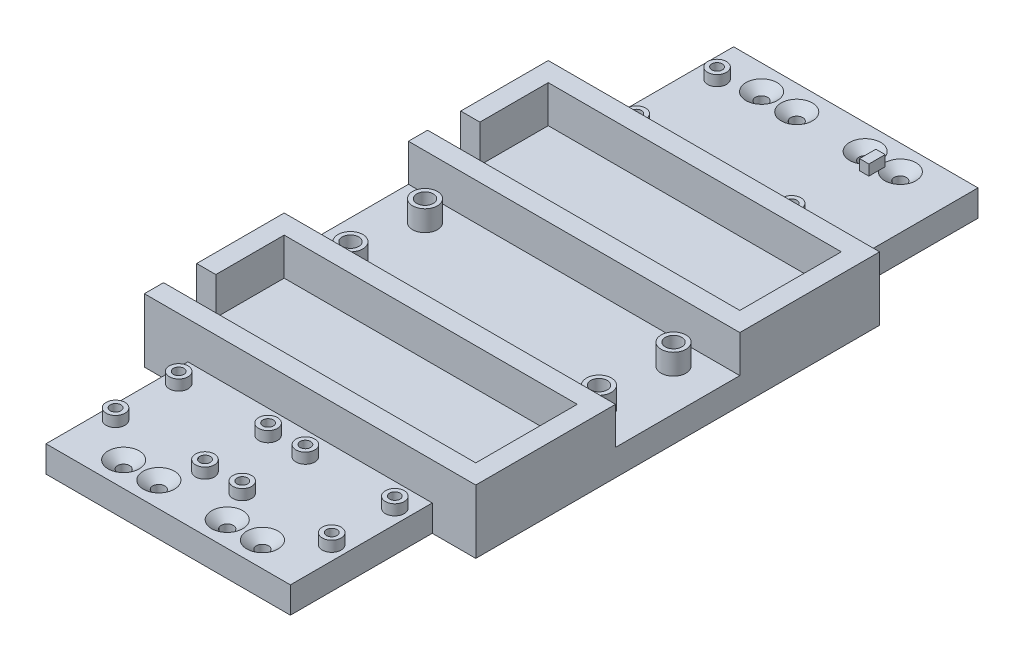
SolidWorks part; units mm, degrees
ref_plane "Front Plane" through (0, 0, 0) normal (0, 0, 1) x (1, 0, 0)
ref_plane "Top Plane" through (0, 0, 0) normal (0, 1, 0) x (1, 0, 0)
ref_plane "Right Plane" through (0, 0, 0) normal (1, 0, 0) x (0, 0, -1)
sketch "Sketch2" plane through (0, 0, 0) normal (0, 1, 0) x (1, 0, 0)
  line L1 (40, -83) -> (-40, -83)
  line L2 (40, -83) -> (40, 83)
  line L3 (40, 83) -> (-40, 83)
  line L4 (-40, -83) -> (-40, 83)
  line L5 (40, -83) -> (-40, 83) construction
  line L6 (40, 83) -> (-40, -83) construction
  point P0 (0, 0)
  dimension "D1" = 80
  dimension "D2" = 166
extrude "Boss-Extrude1" add sketch "Sketch2" along normal blind 6.35
sketch "Sketch3" plane through (0, 6.35, 0) normal (0, 1, 0) x (1, 0, 0)
  line L3 (16.755, 77) -> (8.255, 77)
  line L4 (0, 0) -> (0, 77)
  line L6 (0, 77) -> (8.255, 77)
  dimension "D1" = 8.255
  dimension "D2" = 8.5
  dimension "D3" = 77
hole_wizard "CSK for #4 Flat Head Machine Screw (100)1" positions "Sketch4" profile "Sketch5" countersink size "#4" standard "ANSI Inch" end condition through all
sketch "Sketch4" plane through (0, 6.35, 0) normal (0, 1, 0) x (1, 0, 0)
  point P0 (16.755, 77)
  point P3 (8.255, 77)
sketch "Sketch5" plane through (16.755, 6.35, -77) normal (1, 0, 0) x (0, 0, 1)
  line L0 (0, 0) -> (0, 6.35)
  line L1 (0, 6.35) -> (1.4732, 6.35)
  line L2 (1.4732, 6.35) -> (1.4732, 1.9236)
  line L3 (1.4732, 1.9236) -> (3.7657, 0)
  line L5 (3.7657, 0) -> (0, 0)
  line L6 (-1.4732, 1.9236) -> (-3.7657, 0) construction
  line L11 (0, -6.35) -> (0, 107.95) construction
  dimension "Thru Hole Dia." = 2.9464
  dimension "Thru Hole Depth" = 6.35
  dimension "Near C'Sink Dia." = 7.5313
  dimension "Near C'Sink Angle" = 100
mirror "Mirror1" about plane through (0, 0, 0) normal (0, 0, 1) of "CSK for #4 Flat Head Machine Screw (100)1"
mirror "Mirror2" about plane through (0, 0, 0) normal (1, 0, 0) of "Mirror1", "CSK for #4 Flat Head Machine Screw (100)1"
sketch "Sketch7" plane through (0, 6.35, 0) normal (0, 1, 0) x (1, 0, 0)
  line L0 (-30, 9) -> (30, 9)
  line L1 (30, 9) -> (30, -9)
  line L2 (30, -9) -> (-30, -9)
  line L3 (-30, -9) -> (-30, 9)
  line L4 (-4.5, -69.62) -> (-26.09, -69.62)
  line L5 (-26.09, -69.62) -> (-26.09, -54.38)
  line L6 (-26.09, -54.38) -> (-4.5, -54.38)
  line L7 (-4.5, -54.38) -> (-4.5, -69.62)
  line L8 (4.5, -69.62) -> (4.5, -54.38)
  line L9 (4.5, -54.38) -> (26.09, -54.38)
  line L10 (26.09, -54.38) -> (26.09, -69.62)
  line L11 (26.09, -69.62) -> (4.5, -69.62)
  line L13 (0, -9) -> (0, 0) construction
  line L14 (-24.75, 54.75) -> (12.75, 54.75)
  line L15 (12.75, 54.75) -> (12.75, 74.25)
  line L16 (12.75, 74.25) -> (-24.75, 74.25)
  line L17 (-24.75, 74.25) -> (-24.75, 54.75)
  line L18 (12.75, 64.5) -> (0, 64.5)
  line L19 (0, 0) -> (-30, 0) construction
  line L20 (-4.5, -62) -> (4.5, -62) construction
  line L21 (0, -62) -> (0, -9) construction
  line L22 (0, 64.5) -> (0, 0) construction
  point P14 (4.5, -62)
  dimension "D2" = 64.5
  dimension "D3" = 21.59
  dimension "D4" = 15.24
  dimension "D5" = 18
  dimension "D6" = 19.5
  dimension "D7" = 15.24
  dimension "D8" = 37.5
  dimension "D9" = 9
  dimension "D10" = 60
  dimension "D11" = 53
  dimension "D12" = 12.75
sketch "Sketch9" plane through (0, 6.35, 0) normal (0, 1, 0) x (1, 0, 0)
  circle A0 centre (-30, 9) radius 2
  circle A1 centre (-30, -9) radius 2
  circle A2 centre (30, -9) radius 2
  circle A3 centre (30, 9) radius 2
  circle A4 centre (-30, -9) radius 3
  circle A5 centre (-30, 9) radius 3
  circle A6 centre (30, 9) radius 3
  circle A7 centre (30, -9) radius 3
  dimension "D1" = 4
  dimension "D2" = 1
extrude "Boss-Extrude3" add sketch "Sketch9" along normal blind 5
sketch "Sketch15" plane through (0, 6.35, 0) normal (0, 1, 0) x (1, 0, 0)
  line L0 (-35.375, 44.125) -> (35.375, 44.125)
  line L1 (35.375, 44.125) -> (35.375, 19.625)
  line L2 (35.375, 19.625) -> (-40, 19.625)
  line L3 (-35.375, 27.625) -> (-35.375, 44.125)
  line L4 (35.375, 31.875) -> (40, 31.875) construction
  line L5 (40, 15) -> (-40, 15)
  line L6 (-40, 83) -> (-40, -83) construction
  line L7 (40, -83) -> (40, 83) construction
  line L8 (-40, 15) -> (-40, 19.625)
  line L9 (-40, 48.75) -> (40, 48.75)
  line L10 (40, 48.75) -> (40, 15)
  line L11 (-35.375, 27.625) -> (-40, 27.625)
  line L13 (-40, 27.625) -> (-40, 48.75)
  line L14 (0, 48.75) -> (0, 44.125) construction
  line L15 (0, 15) -> (0, 19.625) construction
  line L16 (0, 15) -> (0, 0) construction
  line L17 (0, 0) -> (0, -15) construction
  line L18 (-40, -15) -> (40, -15)
  line L19 (40, -15) -> (40, -48.75)
  line L20 (40, -48.75) -> (-40, -48.75)
  line L21 (-40, -48.75) -> (-40, -44.125)
  line L22 (-40, -44.125) -> (35.375, -44.125)
  line L23 (35.375, -44.125) -> (35.375, -19.625)
  line L24 (35.375, -19.625) -> (-35.375, -19.625)
  line L25 (-35.375, -19.625) -> (-35.375, -36.125)
  line L26 (-35.375, -36.125) -> (-40, -36.125)
  line L27 (-40, -36.125) -> (-40, -15)
  line L28 (0, -15) -> (0, -19.625) construction
  point P35 (0, -15)
  dimension "D1" = 70.75
  dimension "D2" = 24.5
  dimension "D3" = 15
  dimension "D4" = 8
extrude "Boss-Extrude5" add sketch "Sketch15" along normal blind 9
sketch "Sketch10" plane through (0, 6.35, 0) normal (0, 1, 0) x (1, 0, 0)
  line L1 (11.625, 72.2784) -> (13.875, 72.2784)
  line L2 (11.625, 72.2784) -> (11.625, 76.2216)
  line L3 (11.625, 76.2216) -> (13.875, 76.2216)
  line L4 (13.875, 72.2784) -> (13.875, 76.2216)
  line L5 (11.625, 72.2784) -> (13.875, 76.2216) construction
  line L6 (11.625, 76.2216) -> (13.875, 72.2784) construction
  circle A0 centre (-4.5, -54.38) radius 1.27
  circle A1 centre (-4.5, -69.62) radius 1.27
  circle A2 centre (-26.09, -69.62) radius 1.27
  circle A3 centre (-26.09, -54.38) radius 1.27
  circle A4 centre (4.5, -54.38) radius 1.27
  circle A5 centre (4.5, -69.62) radius 1.27
  circle A6 centre (26.09, -69.62) radius 1.27
  circle A7 centre (26.09, -54.38) radius 1.27
  circle A8 centre (-4.5, -54.38) radius 2.27
  circle A9 centre (-4.5, -69.62) radius 2.27
  circle A10 centre (-26.09, -54.38) radius 2.27
  circle A11 centre (-26.09, -69.62) radius 2.27
  circle A12 centre (4.5, -54.38) radius 2.27
  circle A13 centre (4.5, -69.62) radius 2.27
  circle A14 centre (26.09, -69.62) radius 2.27
  circle A15 centre (26.09, -54.38) radius 2.27
  circle A16 centre (12.75, 54.75) radius 1.27
  circle A17 centre (12.75, 54.75) radius 2.27
  circle A18 centre (12.75, 74.25) radius 1.27 construction
  circle A19 centre (12.75, 74.25) radius 2.27 construction
  circle A20 centre (-24.75, 74.25) radius 1.27
  circle A21 centre (-24.75, 54.75) radius 1.27
  circle A22 centre (-24.75, 54.75) radius 2.27
  circle A23 centre (-24.75, 74.25) radius 2.27
  dimension "D1" = 2.54
  dimension "D2" = 1
  dimension "D3" = 2.25
extrude "Boss-Extrude4" add sketch "Sketch10" along normal blind 2.54
sketch "Sketch11" plane through (0, 6.35, 0) normal (0, 1, 0) x (1, 0, 0)
  circle A0 centre (-30, -9) radius 2
  circle A1 centre (-30, 9) radius 2
  circle A2 centre (26.09, -54.38) radius 1.27
  circle A3 centre (26.09, -69.62) radius 1.27
  circle A4 centre (4.5, -54.38) radius 1.27
  circle A5 centre (4.5, -69.62) radius 1.27
  circle A6 centre (30, 9) radius 2
  circle A7 centre (30, -9) radius 2
  circle A8 centre (-26.09, -69.62) radius 1.27
  circle A9 centre (-26.09, -54.38) radius 1.27
  circle A10 centre (-4.5, -69.62) radius 1.27
  circle A11 centre (-4.5, -54.38) radius 1.27
  circle A12 centre (-30, -9) radius 2 construction
  circle A13 centre (-4.5, -54.38) radius 1.27 construction
  circle A14 centre (12.75, 74.25) radius 1.27 construction
  circle A15 centre (12.75, 54.75) radius 1.27
  circle A16 centre (-24.75, 54.75) radius 1.27
  circle A17 centre (-24.75, 74.25) radius 1.27
extrude "Cut-Extrude1" cut sketch "Sketch11" against normal through all
sketch "Sketch12" plane through (0, 0, 0) normal (0, -1, 0) x (1, 0, 0)
  line L1 (-23.59, 52.9366) -> (-23.59, 55.8234)
  line L2 (-23.59, 55.8234) -> (-26.09, 57.2668)
  line L3 (-26.09, 57.2668) -> (-28.59, 55.8234)
  line L4 (-28.59, 55.8234) -> (-28.59, 52.9366)
  line L5 (-28.59, 52.9366) -> (-26.09, 51.4932)
  line L6 (-26.09, 51.4932) -> (-23.59, 52.9366)
  line L7 (-2, 52.9366) -> (-2, 55.8234)
  line L8 (-2, 55.8234) -> (-4.5, 57.2668)
  line L9 (-4.5, 57.2668) -> (-7, 55.8234)
  line L10 (-7, 55.8234) -> (-7, 52.9366)
  line L11 (-7, 52.9366) -> (-4.5, 51.4932)
  line L12 (-4.5, 51.4932) -> (-2, 52.9366)
  line L13 (-23.59, 68.1766) -> (-23.59, 71.0634)
  line L14 (-23.59, 71.0634) -> (-26.09, 72.5068)
  line L15 (-26.09, 72.5068) -> (-28.59, 71.0634)
  line L16 (-28.59, 71.0634) -> (-28.59, 68.1766)
  line L17 (-28.59, 68.1766) -> (-26.09, 66.7332)
  line L18 (-26.09, 66.7332) -> (-23.59, 68.1766)
  line L19 (-2, 68.1766) -> (-2, 71.0634)
  line L20 (-2, 71.0634) -> (-4.5, 72.5068)
  line L21 (-4.5, 72.5068) -> (-7, 71.0634)
  line L22 (-7, 71.0634) -> (-7, 68.1766)
  line L23 (-7, 68.1766) -> (-4.5, 66.7332)
  line L24 (-4.5, 66.7332) -> (-2, 68.1766)
  line L25 (7, 52.9366) -> (7, 55.8234)
  line L26 (7, 55.8234) -> (4.5, 57.2668)
  line L27 (4.5, 57.2668) -> (2, 55.8234)
  line L28 (2, 55.8234) -> (2, 52.9366)
  line L29 (2, 52.9366) -> (4.5, 51.4932)
  line L30 (4.5, 51.4932) -> (7, 52.9366)
  line L31 (7, 68.1766) -> (7, 71.0634)
  line L32 (7, 71.0634) -> (4.5, 72.5068)
  line L33 (4.5, 72.5068) -> (2, 71.0634)
  line L34 (2, 71.0634) -> (2, 68.1766)
  line L35 (2, 68.1766) -> (4.5, 66.7332)
  line L36 (4.5, 66.7332) -> (7, 68.1766)
  line L37 (28.59, 68.1766) -> (28.59, 71.0634)
  line L38 (28.59, 71.0634) -> (26.09, 72.5068)
  line L39 (26.09, 72.5068) -> (23.59, 71.0634)
  line L40 (23.59, 71.0634) -> (23.59, 68.1766)
  line L41 (23.59, 68.1766) -> (26.09, 66.7332)
  line L42 (26.09, 66.7332) -> (28.59, 68.1766)
  line L43 (28.59, 52.9366) -> (28.59, 55.8234)
  line L44 (28.59, 55.8234) -> (26.09, 57.2668)
  line L45 (26.09, 57.2668) -> (23.59, 55.8234)
  line L46 (23.59, 55.8234) -> (23.59, 52.9366)
  line L47 (23.59, 52.9366) -> (26.09, 51.4932)
  line L48 (26.09, 51.4932) -> (28.59, 52.9366)
  line L49 (-22.25, -75.6934) -> (-22.25, -72.8066)
  line L50 (-22.25, -72.8066) -> (-24.75, -71.3632)
  line L51 (-24.75, -71.3632) -> (-27.25, -72.8066)
  line L52 (-27.25, -72.8066) -> (-27.25, -75.6934)
  line L53 (-27.25, -75.6934) -> (-24.75, -77.1368)
  line L54 (-24.75, -77.1368) -> (-22.25, -75.6934)
  line L55 (-22.25, -56.1934) -> (-22.25, -53.3066)
  line L56 (-22.25, -53.3066) -> (-24.75, -51.8632)
  line L57 (-24.75, -51.8632) -> (-27.25, -53.3066)
  line L58 (-27.25, -53.3066) -> (-27.25, -56.1934)
  line L59 (-27.25, -56.1934) -> (-24.75, -57.6368)
  line L60 (-24.75, -57.6368) -> (-22.25, -56.1934)
  line L61 (15.4277, -75.6934) -> (15.4277, -72.8066) construction
  line L62 (15.4277, -72.8066) -> (12.9277, -71.3632) construction
  line L63 (12.9277, -71.3632) -> (10.4277, -72.8066) construction
  line L64 (10.4277, -72.8066) -> (10.4277, -75.6934) construction
  line L65 (10.4277, -75.6934) -> (12.9277, -77.1368) construction
  line L66 (12.9277, -77.1368) -> (15.4277, -75.6934) construction
  line L67 (15.25, -56.1934) -> (15.25, -53.3066)
  line L68 (15.25, -53.3066) -> (12.75, -51.8632)
  line L69 (12.75, -51.8632) -> (10.25, -53.3066)
  line L70 (10.25, -53.3066) -> (10.25, -56.1934)
  line L71 (10.25, -56.1934) -> (12.75, -57.6368)
  line L72 (12.75, -57.6368) -> (15.25, -56.1934)
  circle A0 centre (-26.09, 54.38) radius 2.5 construction
  circle A1 centre (-4.5, 54.38) radius 2.5 construction
  circle A2 centre (-26.09, 69.62) radius 2.5 construction
  circle A3 centre (-4.5, 69.62) radius 2.5 construction
  circle A4 centre (4.5, 54.38) radius 2.5 construction
  circle A5 centre (4.5, 69.62) radius 2.5 construction
  circle A6 centre (26.09, 69.62) radius 2.5 construction
  circle A7 centre (26.09, 54.38) radius 2.5 construction
  circle A8 centre (-24.75, -74.25) radius 2.5 construction
  circle A9 centre (-24.75, -54.75) radius 2.5 construction
  circle A10 centre (12.9277, -74.25) radius 2.5 construction
  circle A11 centre (12.75, -54.75) radius 2.5 construction
  dimension "D1" = 5
extrude "Cut-Extrude2" cut sketch "Sketch12" against normal offset from surface (2.89 mm away) 6 up to face at (-26.09, 8.89, 56.65)
sketch "Sketch14" plane through (0, 0, 0) normal (0, -1, 0) x (1, 0, 0)
  line L1 (33.175, 7.1669) -> (33.175, 10.8331)
  line L2 (33.175, 10.8331) -> (30, 12.6662)
  line L3 (30, 12.6662) -> (26.825, 10.8331)
  line L4 (26.825, 10.8331) -> (26.825, 7.1669)
  line L5 (26.825, 7.1669) -> (30, 5.3338)
  line L6 (30, 5.3338) -> (33.175, 7.1669)
  line L7 (26.825, -10.8331) -> (30, -12.6662)
  line L8 (30, -12.6662) -> (33.175, -10.8331)
  line L9 (33.175, -10.8331) -> (33.175, -7.1669)
  line L10 (33.175, -7.1669) -> (30, -5.3338)
  line L11 (30, -5.3338) -> (26.825, -7.1669)
  line L12 (26.825, -7.1669) -> (26.825, -10.8331)
  line L13 (-26.825, 10.8331) -> (-30, 12.6662)
  line L14 (-30, 12.6662) -> (-33.175, 10.8331)
  line L15 (-33.175, 10.8331) -> (-33.175, 7.1669)
  line L16 (-33.175, 7.1669) -> (-30, 5.3338)
  line L17 (-30, 5.3338) -> (-26.825, 7.1669)
  line L18 (-26.825, 7.1669) -> (-26.825, 10.8331)
  line L19 (-33.175, -10.8331) -> (-30, -12.6662)
  line L20 (-30, -12.6662) -> (-26.825, -10.8331)
  line L21 (-26.825, -10.8331) -> (-26.825, -7.1669)
  line L22 (-26.825, -7.1669) -> (-30, -5.3338)
  line L23 (-30, -5.3338) -> (-33.175, -7.1669)
  line L24 (-33.175, -7.1669) -> (-33.175, -10.8331)
  circle A0 centre (30, 9) radius 3.175 construction
  circle A1 centre (30, -9) radius 3.175 construction
  circle A2 centre (-30, 9) radius 3.175 construction
  circle A3 centre (-30, -9) radius 3.175 construction
  dimension "D1" = 6.35
sketch "Sketch16" plane through (0, 6.35, 0) normal (0, 1, 0) x (1, 0, 0)
  line L0 (40, 83) -> (-40, 83) construction
  line L1 (29.5, 83) -> (40, 83)
  line L2 (29.5, 83) -> (29.5, 48.75)
  line L3 (29.5, 48.75) -> (40, 48.75)
  line L4 (40, 83) -> (40, 48.75)
  line L5 (29.5, 83) -> (40, 48.75) construction
  line L6 (29.5, 48.75) -> (40, 83) construction
  line L7 (-29.5, 83) -> (-40, 83)
  line L8 (-29.5, 83) -> (-29.5, 48.75)
  line L9 (-29.5, 48.75) -> (-40, 48.75)
  line L10 (-40, 83) -> (-40, 48.75)
  line L11 (-29.5, 83) -> (-40, 48.75) construction
  line L12 (-29.5, 48.75) -> (-40, 83) construction
  line L13 (-40, -83) -> (40, -83) construction
  line L14 (-29.5, -83) -> (-40, -83)
  line L15 (-29.5, -83) -> (-29.5, -48.75)
  line L16 (-29.5, -48.75) -> (-40, -48.75)
  line L17 (-40, -83) -> (-40, -48.75)
  line L18 (-29.5, -83) -> (-40, -48.75) construction
  line L19 (-29.5, -48.75) -> (-40, -83) construction
  line L20 (29.5, -83) -> (40, -83)
  line L21 (29.5, -83) -> (29.5, -48.75)
  line L22 (29.5, -48.75) -> (40, -48.75)
  line L23 (40, -83) -> (40, -48.75)
  line L24 (29.5, -83) -> (40, -48.75) construction
  line L25 (29.5, -48.75) -> (40, -83) construction
  point P0 (34.75, 65.875)
  point P6 (-34.75, 65.875)
  point P14 (-34.75, -65.875)
  point P20 (34.75, -65.875)
  dimension "D1" = 59
  dimension "D2" = 59
extrude "Cut-Extrude4" cut sketch "Sketch16" against normal through all
extrude "Cut-Extrude3" cut sketch "Sketch14" against normal blind 3.81
